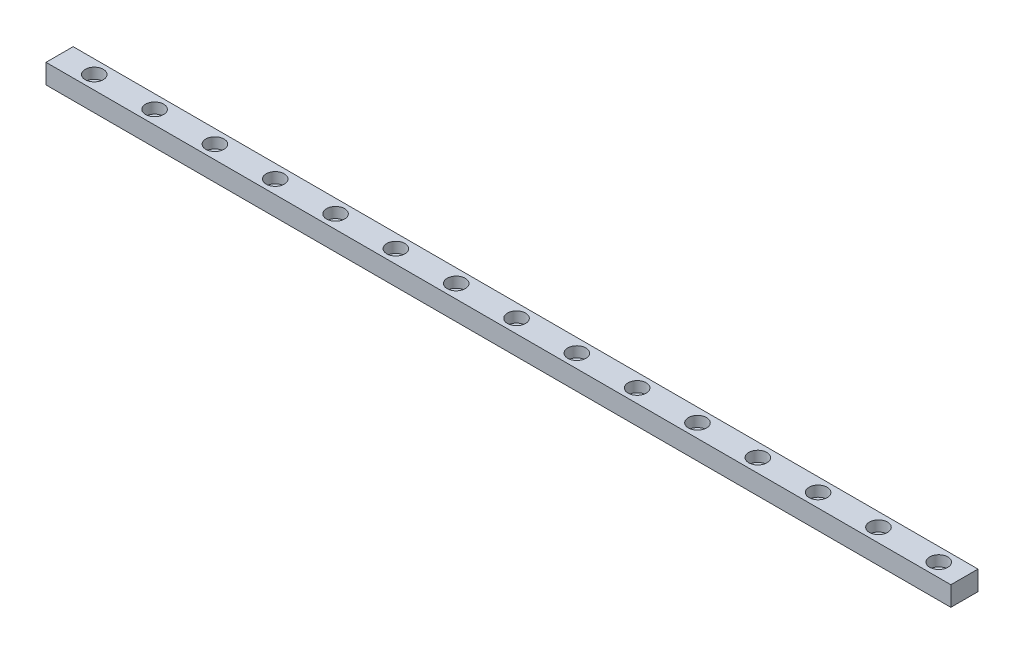
SolidWorks part; units mm, degrees
material "AISI 304"
ref_plane "Front Plane" through (0, 0, 0) normal (0, 0, 1) x (1, 0, 0)
ref_plane "Top Plane" through (0, 0, 0) normal (0, 1, 0) x (1, 0, 0)
ref_plane "Right Plane" through (0, 0, 0) normal (1, 0, 0) x (0, 0, -1)
sketch "Sketch1" plane through (0, 0, 0) normal (1, 0, 0) x (0, 0, -1)
  line L1 (-4.5, 0) -> (-4.5, -6.5)
  line L2 (-4.5, -6.5) -> (4.5, -6.5)
  line L3 (4.5, -6.5) -> (4.5, 0)
  line L4 (4.5, 0) -> (-4.5, 0)
extrude "Boss-Extrude1" add sketch "Sketch1" along normal mid plane 300
sketch "Sketch2" plane through (0, 0, 0) normal (0, 1, 0) x (1, 0, 0)
  circle A0 centre (-138.5, 0) radius 1.5
  circle A1 centre (-118.5, 0) radius 1.5
  circle A2 centre (-98.5, 0) radius 1.5
  circle A3 centre (-78.5, 0) radius 1.5
  circle A4 centre (-58.5, 0) radius 1.5
  circle A5 centre (-38.5, 0) radius 1.5
  circle A6 centre (-18.5, 0) radius 1.5
  circle A7 centre (1.5, 0) radius 1.5
  circle A8 centre (21.5, 0) radius 1.5
  circle A9 centre (41.5, 0) radius 1.5
  circle A10 centre (61.5, 0) radius 1.5
  circle A11 centre (81.5, 0) radius 1.5
  circle A12 centre (101.5, 0) radius 1.5
  circle A13 centre (121.5, 0) radius 1.5
  circle A14 centre (141.5, 0) radius 1.5
  dimension "D1" = 15
extrude "Cut-Extrude1" cut sketch "Sketch2" against normal through all
sketch "Sketch3" plane through (0, 0, 0) normal (0, 1, 0) x (1, 0, 0)
  circle A0 centre (-138.5, 0) radius 3
  circle A1 centre (-118.5, 0) radius 3
  circle A2 centre (-98.5, 0) radius 3
  circle A3 centre (-78.5, 0) radius 3
  circle A4 centre (-58.5, 0) radius 3
  circle A5 centre (-38.5, 0) radius 3
  circle A6 centre (-18.5, 0) radius 3
  circle A7 centre (1.5, 0) radius 3
  circle A8 centre (21.5, 0) radius 3
  circle A9 centre (41.5, 0) radius 3
  circle A10 centre (61.5, 0) radius 3
  circle A11 centre (81.5, 0) radius 3
  circle A12 centre (101.5, 0) radius 3
  circle A13 centre (121.5, 0) radius 3
  circle A14 centre (141.5, 0) radius 3
  dimension "D1" = 15
extrude "Cut-Extrude2" cut sketch "Sketch3" against normal blind 3.5
